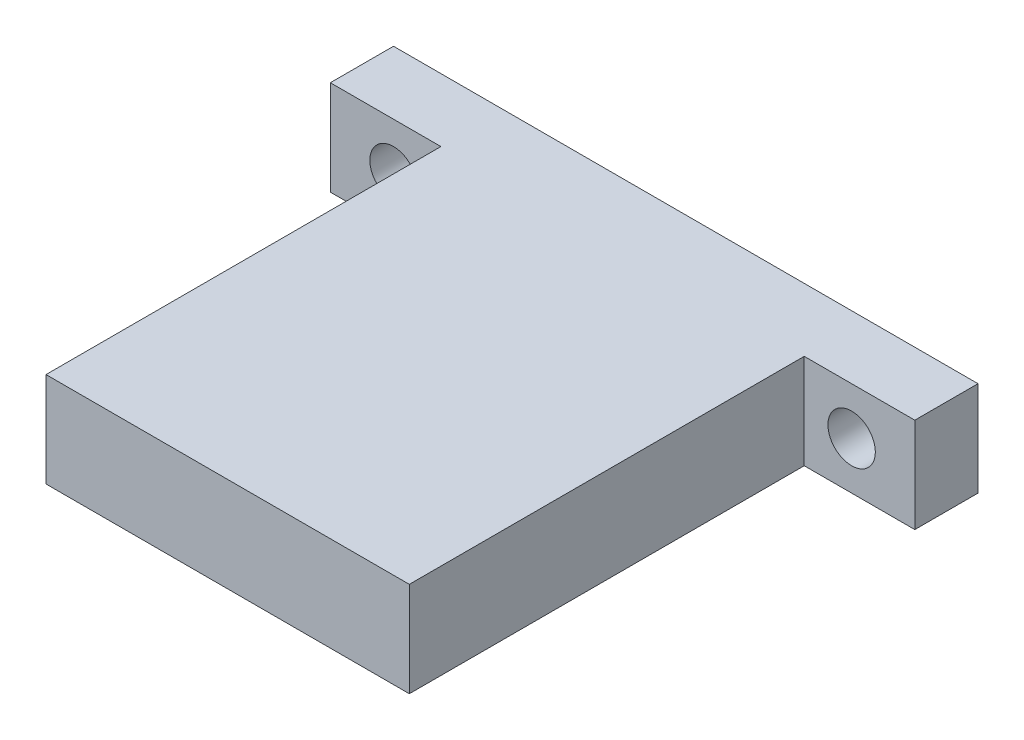
SolidWorks part; units mm, degrees
ref_plane "Alzado" through (0, 0, 0) normal (0, 0, 1) x (1, 0, 0)
ref_plane "Planta" through (0, 0, 0) normal (0, 1, 0) x (1, 0, 0)
ref_plane "Vista lateral" through (0, 0, 0) normal (1, 0, 0) x (0, 0, -1)
sketch "Croquis1" plane through (0, 0, 0) normal (0, 0, 1) x (1, 0, 0)
  line L1 (-37.3458, 16.4019) -> (-0.3458, 16.4019)
  line L2 (-37.3458, 16.4019) -> (-37.3458, 6.4019)
  line L3 (-37.3458, 6.4019) -> (-0.3458, 6.4019)
  line L4 (-0.3458, 16.4019) -> (-0.3458, 6.4019)
  dimension "D1" = 10
  dimension "D2" = 37
extrude "Saliente-Extruir1" add sketch "Croquis1" along normal blind 25
sketch "Croquis2" plane through (0, 0, 25) normal (0, 0, 1) x (1, 0, 0)
  line L0 (-0.3458, 6.4019) -> (-0.3458, 16.4019) construction
  line L1 (-37.3458, 6.4019) -> (-0.3458, 6.4019)
  line L2 (-37.3458, 6.4019) -> (-37.3458, 12.4019)
  line L3 (-37.3458, 12.4019) -> (-0.3458, 12.4019)
  line L4 (-0.3458, 6.4019) -> (-0.3458, 12.4019)
  line L5 (-0.3458, 16.4019) -> (-37.3458, 16.4019) construction
  dimension "D1" = 4
extrude "Cortar-Extruir1" cut sketch "Croquis2" against normal blind 21
sketch "Croquis4" plane through (0, 0, 4) normal (0, 0, 1) x (1, 0, 0)
  line L0 (-37.3458, 6.4019) -> (-0.3458, 6.4019) construction
  line L2 (-37.3458, 12.4019) -> (-37.3458, 6.4019) construction
  circle A0 centre (-33.3458, 9.4019) radius 1.5
  circle A1 centre (-4.3458, 9.4019) radius 1.5
  dimension "D1" = 29
  dimension "D2" = 3
  dimension "D3" = 3
  dimension "D4" = 4
extrude "Cortar-Extruir2" cut sketch "Croquis4" against normal up to vertex (4 mm away)
sketch "Croquis6" plane through (0, 0, 0) normal (0, 0, -1) x (-1, 0, 0)
  line L0 (37.3458, 16.4019) -> (37.3458, 6.4019) construction
  line L1 (0.3458, 16.4019) -> (37.3458, 16.4019)
  line L2 (0.3458, 16.4019) -> (0.3458, 12.4019)
  line L3 (0.3458, 12.4019) -> (37.3458, 12.4019)
  line L4 (37.3458, 16.4019) -> (37.3458, 12.4019)
  dimension "D1" = 4
extrude "Cortar-Extruir3" cut sketch "Croquis6" against normal up to vertex (4 mm away)
sketch "Croquis8" plane through (0, 0, 4) normal (0, 0, 1) x (1, 0, 0)
  line L0 (-0.3458, 12.4019) -> (-37.3458, 12.4019) construction
  line L1 (-30.3458, 12.4019) -> (-7.3458, 12.4019)
  line L2 (-30.3458, 12.4019) -> (-30.3458, 6.4019)
  line L3 (-30.3458, 6.4019) -> (-7.3458, 6.4019)
  line L4 (-7.3458, 12.4019) -> (-7.3458, 6.4019)
  line L5 (-37.3458, 6.4019) -> (-0.3458, 6.4019) construction
extrude "Saliente-Extruir2" add sketch "Croquis8" along normal blind 25
